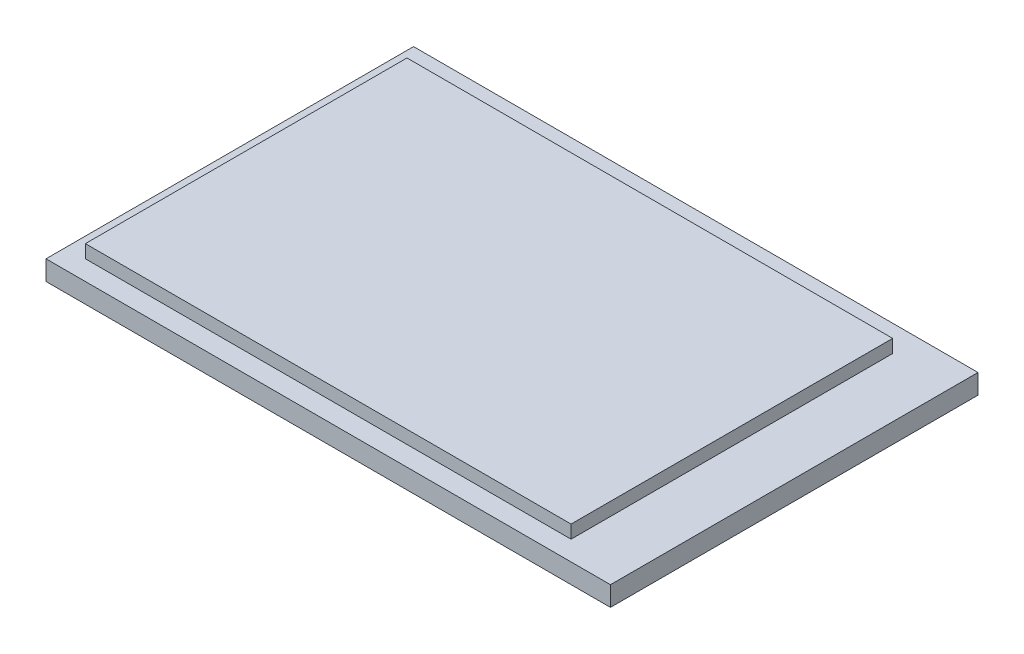
SolidWorks part; units mm, degrees
ref_plane "Front Plane" through (0, 0, 0) normal (0, 0, 1) x (1, 0, 0)
ref_plane "Top Plane" through (0, 0, 0) normal (0, 1, 0) x (1, 0, 0)
ref_plane "Right Plane" through (0, 0, 0) normal (1, 0, 0) x (0, 0, -1)
sketch "Sketch1" plane through (0, 0, 0) normal (0, 1, 0) x (1, 0, 0)
  line L1 (-37, -24.5) -> (37, -24.5)
  line L2 (-37, -24.5) -> (-37, 24.5)
  line L3 (-37, 24.5) -> (37, 24.5)
  line L4 (37, -24.5) -> (37, 24.5)
  line L5 (-37, -24.5) -> (37, 24.5) construction
  line L6 (-37, 24.5) -> (37, -24.5) construction
  point P0 (0, 0)
  dimension "D1" = 74
  dimension "D2" = 49
extrude "Boss-Extrude1" add sketch "Sketch1" along normal blind 2
sketch "Sketch2" plane through (0, 0, 0) normal (0, -1, 0) x (1, 0, 0)
  line L0 (37, 24.5) -> (37, -24.5) construction
  line L1 (-40, -28.5) -> (46, -28.5)
  line L2 (-40, -28.5) -> (-40, 27.5)
  line L3 (-40, 27.5) -> (46, 27.5)
  line L4 (46, -28.5) -> (46, 27.5)
  line L5 (-40, -28.5) -> (46, 27.5) construction
  line L6 (-40, 27.5) -> (46, -28.5) construction
  line L7 (-37, 24.5) -> (37, 24.5) construction
  point P0 (3, -0.5)
  dimension "D1" = 86
  dimension "D2" = 56
  dimension "D3" = 9
  dimension "D4" = 3
extrude "Boss-Extrude2" add sketch "Sketch2" along normal blind 3 separate body
equation "\"LCD_width\"=74"
equation "\"LCD_height\"=49"
equation "\"LCD_PCB_width\"=86"
equation "\"LCD_PCB_height\"=56"
equation "\"LCD_thickness\"=5"
equation "\"D1@Sketch1\"=\"LCD_width\""
equation "\"D2@Sketch1\"=\"LCD_height\""
equation "\"D1@Sketch2\"=\"LCD_PCB_width\""
equation "\"D2@Sketch2\"=\"LCD_PCB_height\""
